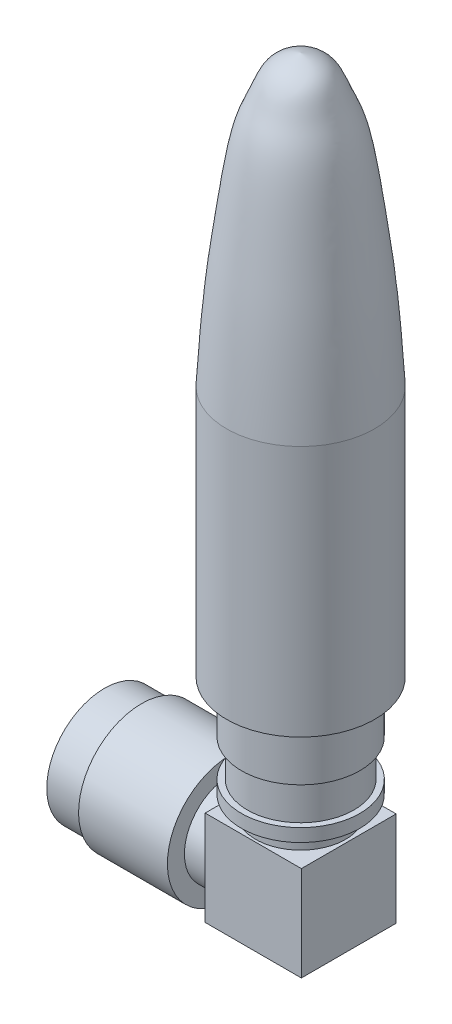
SolidWorks part; units mm, degrees
ref_plane "前视基准面" through (0, 0, 0) normal (0, 0, 1) x (1, 0, 0)
ref_plane "上视基准面" through (0, 0, 0) normal (0, 1, 0) x (1, 0, 0)
ref_plane "右视基准面" through (0, 0, 0) normal (1, 0, 0) x (0, 0, -1)
sketch "草图1" plane through (0, 0, 0) normal (0, 0, 1) x (1, 0, 0)
  line L0 (0, -22.6951) -> (0, 60.3814) construction
  line L1 (0, 0) -> (-3.0367, 0)
  line L2 (-3.0367, 0) -> (-3.0367, 1.1257)
  line L3 (-3.0367, 1.1257) -> (-4, 1.1257)
  line L4 (-4, 1.1257) -> (-4, 2)
  line L5 (-4, 2) -> (-3.6, 2)
  line L6 (-3.6, 2) -> (-3.6, 4.5)
  line L7 (-3.6, 4.5) -> (-4, 4.5)
  line L8 (-4, 4.5) -> (-4, 8)
  line L9 (-4, 8) -> (-5, 8)
  line L10 (-5, 8) -> (-5, 25)
  line L11 (0, 0) -> (0, 44.5)
  spline S0 degree 3 poles (-5, 25) (-4.7222, 30.0335) (-3.7748, 37.407) (-3.3708, 40.0755) (-1.977, 43.1403) (-1.8961, 44.0308) (0, 44.5) knots 0 0 0 0 0.132032 0.478362 0.569488 1 1 1 1
  dimension "D1" = 3.6
  dimension "D2" = 4
  dimension "D3" = 8
  dimension "D4" = 2.5
  dimension "D5" = 3.5
  dimension "D6" = 5
  dimension "D7" = 17
  dimension "D8" = 44.5
revolve "旋转1" add sketch "草图1" angle 360 about L0
sketch "草图2" plane through (0, 0, 0) normal (0, -1, 0) x (1, 0, 0)
  line L0 (0, 6.6168) -> (0, -7.9935) construction
  line L2 (-3.25, 3.2) -> (3.25, 3.2)
  line L3 (-3.25, 3.2) -> (-3.25, -3.2)
  line L4 (-3.25, -3.2) -> (3.25, -3.2)
  line L5 (-9.3984, 0) -> (10.5503, 0) construction
  line L6 (3.25, 3.2) -> (3.25, -3.2)
  dimension "D1" = 6.5
  dimension "D2" = 6.4
extrude "凸台-拉伸1" add sketch "草图2" along normal blind 6.4
sketch "草图4" plane through (0, 0, 0) normal (0, 0, 1) x (1, 0, 0)
  line L0 (-3.25, -3.2) -> (-21.2315, -3.2) construction
  line L2 (-3.25, -0.1) -> (-4.75, -0.1)
  line L3 (-4.75, -0.1) -> (-4.75, 1.05)
  line L4 (-4.75, 1.05) -> (-10.75, 1.05)
  line L5 (-10.75, 1.05) -> (-10.75, 0.7)
  line L6 (-10.75, 0.7) -> (-13.25, 0.7)
  line L7 (-13.25, 0.7) -> (-13.25, -3.2)
  line L8 (-13.25, -3.2) -> (-3.25, -3.2)
  line L9 (-3.25, -3.2) -> (-3.25, -0.1)
  line L10 (-3.25, -6.4) -> (-3.25, 0) construction
  line L13 (3.25, 0) -> (-3.25, 0) construction
  line L14 (3.25, -6.4) -> (-3.25, -6.4) construction
  dimension "D1" = 3.1
  dimension "D2" = 1.5
  dimension "D3" = 6
  dimension "D4" = 4.25
  dimension "D5" = 3.9
  dimension "D6" = 10
revolve "旋转4" add sketch "草图4" angle 360 about L0
sketch "草图5" plane through (-13.25, 0, 0) normal (-1, 0, 0) x (0, 0, 1)
  circle A0 centre (0, -3.2) radius 2.7
  dimension "D1" = 5.4
extrude "切除-拉伸1" cut sketch "草图5" against normal blind 5
